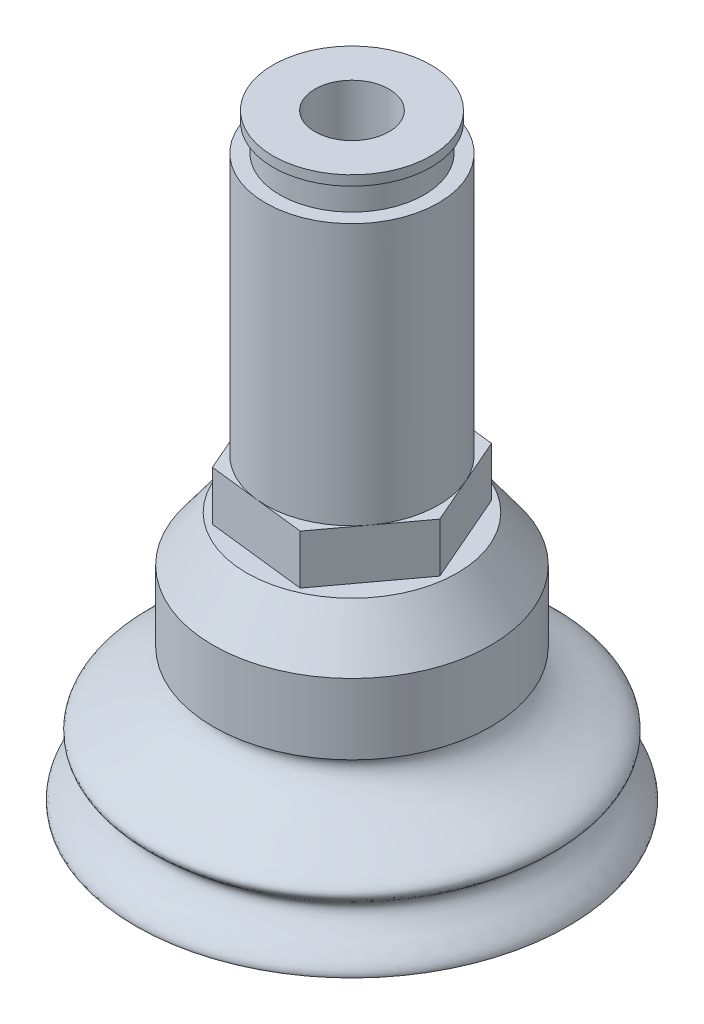
SolidWorks part; units mm, degrees
ref_plane "前视基准面" through (0, 0, 0) normal (0, 0, 1) x (1, 0, 0)
ref_plane "上视基准面" through (0, 0, 0) normal (0, 1, 0) x (1, 0, 0)
ref_plane "右视基准面" through (0, 0, 0) normal (1, 0, 0) x (0, 0, -1)
sketch "草图1" plane through (0, 0, 0) normal (0, 0, 1) x (1, 0, 0)
  line L0 (0, 56.8253) -> (0, -53.2334) construction
  line L1 (0, -11.728) -> (-8.5264, -11.728)
  line L2 (-8.5264, -11.728) -> (-11.2476, -15.435)
  line L3 (-11.2476, -15.435) -> (-11.2476, -21.1464)
  line L4 (0, -11.728) -> (0, -13.4726)
  line L5 (0, -13.4726) -> (-8.2689, -13.4726)
  line L6 (-8.2689, -13.4726) -> (-10.0452, -16.1113)
  line L7 (-10.0452, -16.1113) -> (-10.0452, -19.846)
  line L8 (-10.0452, -19.846) -> (-8.2689, -20.4549)
  line L9 (-8.2689, -20.4549) -> (-8.2689, -26.1381)
  line L10 (-8.2689, -26.1381) -> (-16.2976, -32.028)
  line L11 (-16.2976, -32.028) -> (-17.5, -32.028)
  spline S0 degree 3 poles (-11.2476, -21.1464) (-9.3691, -21.8009) (-10.8897, -25.0793) (-18.5193, -26.3824) (-13.6576, -29.0451) (-17.7283, -31.0728) (-17.5, -32.028) knots 0 0 0 0 0.239283 0.633273 0.728834 1 1 1 1
  dimension "D1" = 17.5
  dimension "D2" = 20.3
revolve "旋转1" add sketch "草图1" angle 360 about L0
sketch "草图2" plane through (0, -11.728, 0) normal (0, 1, 0) x (1, 0, 0)
  line L1 (4.8105, 6.4955) -> (-3.22, 7.4138)
  line L2 (-3.22, 7.4138) -> (-8.0306, 0.9183)
  line L3 (-8.0306, 0.9183) -> (-4.8105, -6.4955)
  line L4 (-4.8105, -6.4955) -> (3.22, -7.4138)
  line L5 (3.22, -7.4138) -> (8.0306, -0.9183)
  line L6 (8.0306, -0.9183) -> (4.8105, 6.4955)
  circle A0 centre (0, 0) radius 7 construction
  dimension "D1" = 14
extrude "凸台-拉伸1" add sketch "草图2" along normal blind 4
sketch "草图3" plane through (0, -7.728, 0) normal (0, 1, 0) x (1, 0, 0)
  circle A0 centre (0, 0) radius 7
  dimension "D1" = 14
extrude "凸台-拉伸2" add sketch "草图3" along normal blind 21.2
sketch "草图4" plane through (0, 13.472, 0) normal (0, 1, 0) x (1, 0, 0)
  circle A0 centre (0, 0) radius 5.8515
extrude "凸台-拉伸3" add sketch "草图4" along normal blind 2.2
sketch "草图5" plane through (0, 15.672, 0) normal (0, 1, 0) x (1, 0, 0)
  circle A0 centre (0, 0) radius 6.393
extrude "凸台-拉伸4" add sketch "草图5" along normal blind 0.8
sketch "草图6" plane through (0, 16.472, 0) normal (0, 1, 0) x (1, 0, 0)
  circle A0 centre (0, 0) radius 3
  dimension "D1" = 6
extrude "切除-拉伸1" cut sketch "草图6" against normal blind 58.8
